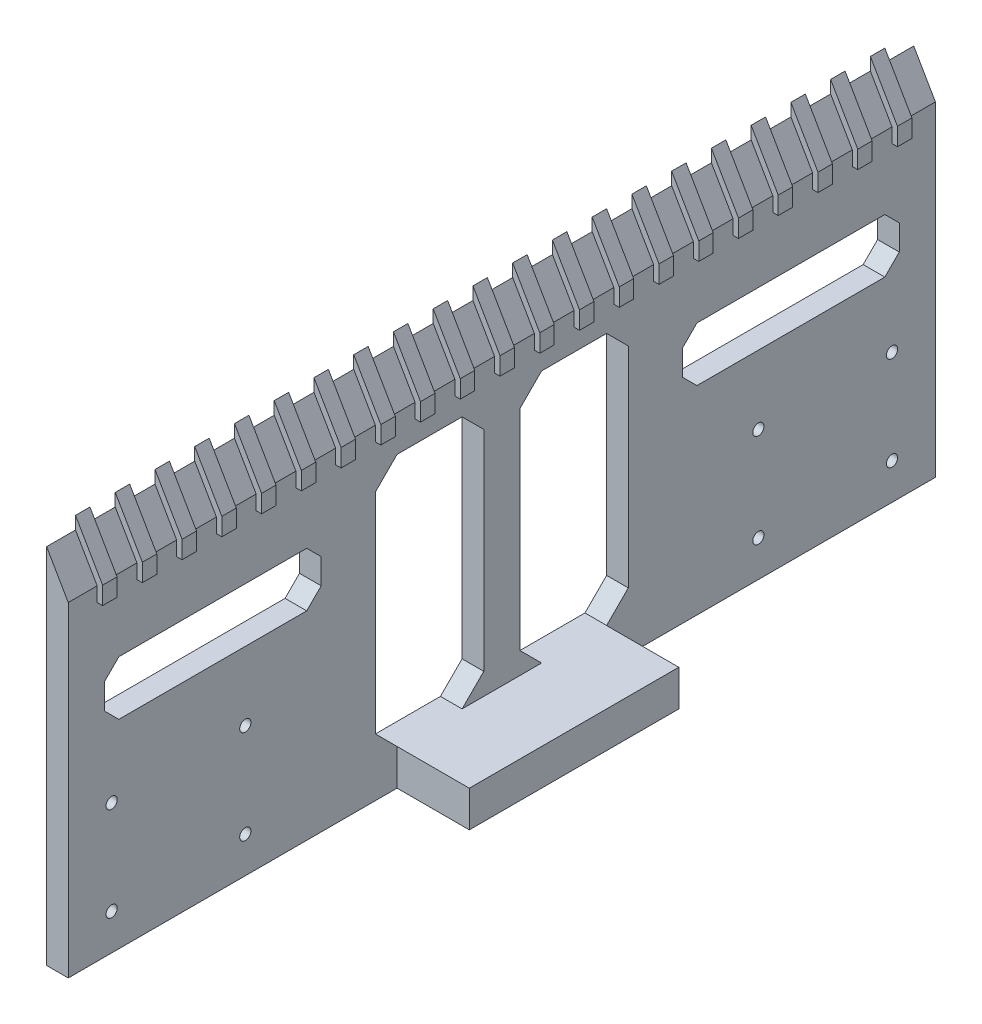
SolidWorks part; units mm, degrees
ref_plane "前视基准面" through (0, 0, 0) normal (0, 0, 1) x (1, 0, 0)
ref_plane "上视基准面" through (0, 0, 0) normal (0, 1, 0) x (1, 0, 0)
ref_plane "右视基准面" through (0, 0, 0) normal (1, 0, 0) x (0, 0, -1)
sketch "草图1" plane through (0, 0, 0) normal (1, 0, 0) x (0, 0, -1)
  line L1 (0, 0) -> (240, 0)
  line L2 (0, 0) -> (0, -90)
  line L3 (0, -90) -> (240, -90)
  line L4 (240, 0) -> (240, -90)
  dimension "D1" = 240
  dimension "D2" = 90
extrude "凸台-拉伸1" add sketch "草图1" along normal blind 6
sketch "草图2" plane through (6, 0, 0) normal (1, 0, 0) x (0, 0, -1)
  line L0 (0, 0) -> (0, -90) construction
  line L1 (12, -54) -> (49, -54) construction
  line L2 (12, -54) -> (12, -80) construction
  line L3 (12, -80) -> (49, -80) construction
  line L4 (49, -54) -> (49, -80) construction
  line L5 (240, 0) -> (0, 0) construction
  line L6 (120, 0) -> (120, -90) construction
  line L7 (0, -90) -> (240, -90) construction
  line L8 (191, -54) -> (191, -80) construction
  line L9 (228, -80) -> (191, -80) construction
  line L10 (228, -54) -> (228, -80) construction
  line L11 (228, -54) -> (191, -54) construction
  circle A0 centre (12, -54) radius 1.55
  circle A1 centre (49, -80) radius 1.55
  circle A2 centre (49, -54) radius 1.55
  circle A3 centre (12, -80) radius 1.55
  circle A4 centre (228, -80) radius 1.55
  circle A5 centre (191, -54) radius 1.55
  circle A6 centre (191, -80) radius 1.55
  circle A7 centre (228, -54) radius 1.55
  dimension "D5" = 3.1
  dimension "D1" = 12
  dimension "D2" = 54
  dimension "D3" = 37
  dimension "D4" = 26
extrude "切除-拉伸1" cut sketch "草图2" against normal through all
sketch "草图3" plane through (6, 0, 0) normal (1, 0, 0) x (0, 0, -1)
  line L0 (120, 0) -> (120, -90) construction
  line L1 (10, -20) -> (70, -20)
  line L2 (10, -20) -> (10, -35)
  line L3 (10, -35) -> (70, -35)
  line L4 (70, -20) -> (70, -35)
  line L5 (240, 0) -> (0, 0) construction
  line L6 (0, -90) -> (240, -90) construction
  line L7 (0, 0) -> (0, -90) construction
  line L8 (170, -20) -> (170, -35)
  line L9 (230, -35) -> (170, -35)
  line L10 (230, -20) -> (230, -35)
  line L11 (230, -20) -> (170, -20)
  dimension "D1" = 10
  dimension "D2" = 20
  dimension "D3" = 15
  dimension "D4" = 60
extrude "切除-拉伸2" cut sketch "草图3" against normal through all
sketch "草图4" plane through (6, 0, 0) normal (1, 0, 0) x (0, 0, -1)
  line L0 (120, 0) -> (120, -90) construction
  line L1 (85, -10) -> (115, -10)
  line L2 (85, -10) -> (85, -80)
  line L3 (85, -80) -> (115, -80)
  line L4 (115, -10) -> (115, -80)
  line L5 (240, 0) -> (0, 0) construction
  line L6 (0, -90) -> (240, -90) construction
  line L7 (0, 0) -> (0, -90) construction
  line L8 (125, -10) -> (125, -80)
  line L9 (155, -80) -> (125, -80)
  line L10 (155, -10) -> (155, -80)
  line L11 (155, -10) -> (125, -10)
  dimension "D1" = 10
  dimension "D2" = 70
  dimension "D3" = 85
  dimension "D4" = 30
extrude "切除-拉伸3" cut sketch "草图4" against normal through all contours L4 L1 L2 L3 | L8 L9 L10 L11
sketch "草图5" plane through (0, 0, 0) normal (-1, 0, 0) x (0, 0, 1)
  circle A0 centre (-191, -80) radius 3
  circle A1 centre (-228, -80) radius 3
  circle A2 centre (-191, -54) radius 3
  circle A3 centre (-228, -54) radius 3
  circle A4 centre (-45, -80) radius 3
  circle A5 centre (-12, -80) radius 3
  circle A6 centre (-12, -54) radius 3
  circle A7 centre (-49, -54) radius 3
  dimension "D1" = 6
extrude "切除-拉伸4" cut sketch "草图5" against normal blind 3
sketch "草图6" plane through (0, 0, 0) normal (0, 0, 1) x (1, 0, 0)
  line L0 (6, 0) -> (0, 0)
  line L1 (0, 0) -> (0, 10.3923)
  line L2 (0, 10.3923) -> (6, 0)
  dimension "D1" = 30
extrude "凸台-拉伸2" add sketch "草图6" against normal blind 240
ref_plane "基准面1" through (0, 0, -120) normal (0, 0, 1) x (1, 0, 0)
chamfer "倒角1" distance 4 angle 45 8 edges at (3, -35, -170) (3, -35, -230) (3, -20, -230) (3, -20, -170) (3, -35, -70) (3, -20, -70) (3, -35, -10) (3, -20, -10)
chamfer "倒角2" distance 6 angle 45 8 edges at (3, -80, -125) (3, -10, -155) (3, -10, -125) (3, -80, -155) (3, -80, -115) (3, -80, -85) (3, -10, -115) (3, -10, -85)
sketch "草图8" plane through (0, 0, -120) normal (0, 0, 1) x (1, 0, 0)
  line L0 (0, 10.3923) -> (0, 13.8923)
  line L1 (0, 13.8923) -> (7.5, 0.9019)
  line L2 (7.5, 0.9019) -> (7.5, -4)
  line L3 (7.5, -4) -> (6, -4)
  line L4 (6, 0) -> (6, -90) construction
  line L5 (6, -4) -> (6, 0)
  line L6 (6, 0) -> (0, 10.3923) construction
  line L7 (6, 0) -> (0, 10.3923)
  dimension "D1" = 3.5
  dimension "D2" = 1.5
  dimension "D3" = 4
extrude "凸台-拉伸3" add sketch "草图8" along normal mid plane 4
pattern_linear "阵列(线性)1" count 11 spacing 11 along (0, 0, 1) count 11 spacing 11 along (0, 0, -1) of "凸台-拉伸3"
sketch "草图9" plane through (6, 0, 0) normal (1, 0, 0) x (0, 0, -1)
  line L0 (0, -90) -> (240, -90) construction
  line L1 (91, -80) -> (148.9732, -80)
  line L2 (91, -80) -> (91, -90)
  line L3 (91, -90) -> (148.9732, -90)
  line L4 (148.9732, -80) -> (148.9732, -90)
extrude "凸台-拉伸4" add sketch "草图9" along normal blind 20
